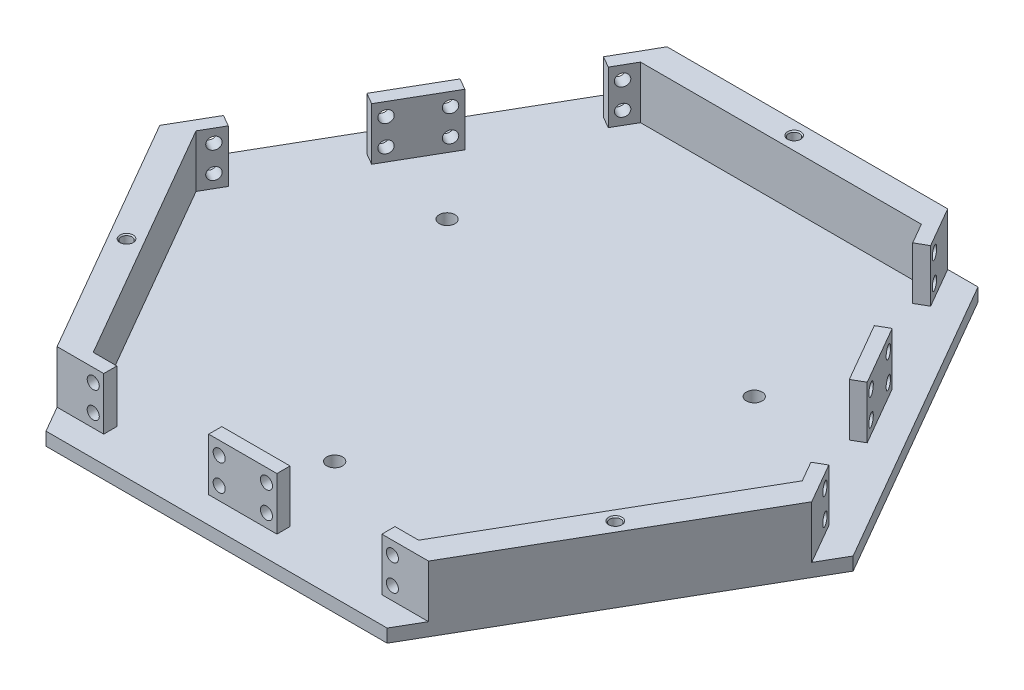
SolidWorks part; units mm, degrees
ref_plane "前视基准面" through (0, 0, 0) normal (0, 0, 1) x (1, 0, 0)
ref_plane "上视基准面" through (0, 0, 0) normal (0, 1, 0) x (1, 0, 0)
ref_plane "右视基准面" through (0, 0, 0) normal (1, 0, 0) x (0, 0, -1)
other "Configuration Table"
sketch "草图6" plane through (0, 0, 0) normal (0, 1, 0) x (1, 0, 0)
  line L1 (130, 0) -> (65, 112.5833)
  line L2 (65, 112.5833) -> (-65, 112.5833)
  line L3 (-65, 112.5833) -> (-130, 0)
  line L4 (-130, 0) -> (-65, -112.5833)
  line L5 (-65, -112.5833) -> (65, -112.5833)
  line L6 (65, -112.5833) -> (130, 0)
  circle A0 centre (0, 0) radius 112.5833 construction
  dimension "D1" = 130
extrude "凸台-拉伸5" add sketch "草图6" along normal blind 5
sketch "草图7" plane through (0, 5, 0) normal (0, 1, 0) x (1, 0, 0)
  line L0 (-53, -112.5833) -> (-13, -112.5833) construction
  line L1 (-53, -112.5833) -> (-53, -72.5833) construction
  line L2 (-13, -112.5833) -> (-13, -72.5833) construction
  line L3 (-53, -72.5833) -> (-13, -72.5833) construction
  line L4 (-65, -112.5833) -> (65, -112.5833) construction
  line L5 (13, -112.5833) -> (53, -112.5833) construction
  line L6 (13, -112.5833) -> (13, -72.5833) construction
  line L7 (53, -112.5833) -> (53, -72.5833) construction
  line L8 (13, -72.5833) -> (53, -72.5833) construction
  line L9 (-71, 102.191) -> (-91, 67.55) construction
  line L10 (-71, 102.191) -> (-36.359, 82.191) construction
  line L11 (-91, 67.55) -> (-56.359, 47.55) construction
  line L12 (-36.359, 82.191) -> (-56.359, 47.55) construction
  line L13 (-65, 112.5833) -> (-130, 0) construction
  line L14 (-104, 45.0333) -> (-124, 10.3923) construction
  line L15 (-104, 45.0333) -> (-69.359, 25.0333) construction
  line L16 (-124, 10.3923) -> (-89.359, -9.6077) construction
  line L17 (-69.359, 25.0333) -> (-89.359, -9.6077) construction
  line L18 (71, 102.191) -> (91, 67.55) construction
  line L19 (71, 102.191) -> (36.359, 82.191) construction
  line L20 (91, 67.55) -> (56.359, 47.55) construction
  line L21 (36.359, 82.191) -> (56.359, 47.55) construction
  line L22 (130, 0) -> (65, 112.5833) construction
  line L23 (104, 45.0333) -> (124, 10.3923) construction
  line L24 (104, 45.0333) -> (69.359, 25.0333) construction
  line L25 (124, 10.3923) -> (89.359, -9.6077) construction
  line L26 (69.359, 25.0333) -> (89.359, -9.6077) construction
  line L27 (-4, -97.5833) -> (4, -97.5833)
  line L28 (-53, -97.5833) -> (-53, -102.5833)
  line L29 (-53, -97.5833) -> (-62, -97.5833)
  line L30 (-53, -102.5833) -> (-62, -102.5833)
  line L31 (-62, -97.5833) -> (-62, -102.5833)
  line L32 (-13, -97.5833) -> (-4, -97.5833)
  line L33 (-13, -97.5833) -> (-13, -102.5833)
  line L34 (-4, -97.5833) -> (-4, -102.5833)
  line L35 (-13, -102.5833) -> (-4, -102.5833)
  line L36 (0, -112.5833) -> (0, 112.5833) construction
  line L37 (65, 112.5833) -> (-65, 112.5833) construction
  line L38 (-115.3397, 5.3923) -> (-111.0096, 2.8923)
  line L39 (-115.3397, 5.3923) -> (-119.8397, -2.4019)
  line L40 (-111.0096, 2.8923) -> (-115.5096, -4.9019)
  line L41 (-119.8397, -2.4019) -> (-115.5096, -4.9019)
  line L42 (-95.3397, 40.0333) -> (-91.0096, 37.5333)
  line L43 (-95.3397, 40.0333) -> (-90.3397, 48.6936)
  line L44 (-91.0096, 37.5333) -> (-86.0096, 46.1936)
  line L45 (-90.3397, 48.6936) -> (-86.0096, 46.1936)
  line L46 (-82.3397, 62.55) -> (-78.0096, 60.05)
  line L47 (-82.3397, 62.55) -> (-86.8397, 54.7558)
  line L48 (-78.0096, 60.05) -> (-82.5096, 52.2558)
  line L49 (-86.8397, 54.7558) -> (-82.5096, 52.2558)
  line L50 (-62.3397, 97.191) -> (-58.0096, 94.691)
  line L51 (-62.3397, 97.191) -> (-57.8397, 104.9852)
  line L52 (-58.0096, 94.691) -> (-53.5096, 102.4852)
  line L53 (-57.8397, 104.9852) -> (-53.5096, 102.4852)
  line L54 (58.0096, 94.691) -> (53.5096, 102.4852)
  line L55 (57.8397, 104.9852) -> (53.5096, 102.4852)
  line L56 (62.3397, 97.191) -> (57.8397, 104.9852)
  line L57 (62.3397, 97.191) -> (58.0096, 94.691)
  line L58 (78.0096, 60.05) -> (82.5096, 52.2558)
  line L59 (86.8397, 54.7558) -> (82.5096, 52.2558)
  line L60 (82.3397, 62.55) -> (86.8397, 54.7558)
  line L61 (82.3397, 62.55) -> (78.0096, 60.05)
  line L62 (91.0096, 37.5333) -> (86.0096, 46.1936)
  line L63 (90.3397, 48.6936) -> (86.0096, 46.1936)
  line L64 (95.3397, 40.0333) -> (90.3397, 48.6936)
  line L65 (95.3397, 40.0333) -> (91.0096, 37.5333)
  line L66 (111.0096, 2.8923) -> (115.5096, -4.9019)
  line L67 (119.8397, -2.4019) -> (115.5096, -4.9019)
  line L68 (115.3397, 5.3923) -> (119.8397, -2.4019)
  line L69 (115.3397, 5.3923) -> (111.0096, 2.8923)
  line L70 (53, -102.5833) -> (62, -102.5833)
  line L71 (62, -97.5833) -> (62, -102.5833)
  line L72 (53, -97.5833) -> (62, -97.5833)
  line L73 (53, -97.5833) -> (53, -102.5833)
  line L74 (4, -97.5833) -> (4, -102.5833)
  line L75 (13, -102.5833) -> (4, -102.5833)
  line L76 (13, -97.5833) -> (13, -102.5833)
  line L77 (13, -97.5833) -> (4, -97.5833)
  line L78 (-4, -97.5833) -> (-4, -102.5833)
  line L79 (4, -97.5833) -> (4, -102.5833)
  line L80 (-4, -102.5833) -> (4, -102.5833)
  line L81 (86.8397, 54.7558) -> (90.3397, 48.6936)
  line L82 (86.8397, 54.7558) -> (82.5096, 52.2558)
  line L83 (90.3397, 48.6936) -> (86.0096, 46.1936)
  line L84 (82.5096, 52.2558) -> (86.0096, 46.1936)
  line L85 (-82.5096, 52.2558) -> (-86.0096, 46.1936)
  line L86 (-82.5096, 52.2558) -> (-86.8397, 54.7558)
  line L87 (-86.0096, 46.1936) -> (-90.3397, 48.6936)
  line L88 (-86.8397, 54.7558) -> (-90.3397, 48.6936)
  dimension "D1" = 40
  dimension "D2" = 40
  dimension "D3" = 40
  dimension "D4" = 40
  dimension "D5" = 40
  dimension "D6" = 40
  dimension "D7" = 40
  dimension "D8" = 40
  dimension "D9" = 40
  dimension "D10" = 40
  dimension "D11" = 40
  dimension "D12" = 40
  dimension "D13" = 12
  dimension "D14" = 12
  dimension "D15" = 12
  dimension "D16" = 12
  dimension "D17" = 12
  dimension "D18" = 12
  dimension "D19" = 9
  dimension "D20" = 5
  dimension "D21" = 10
  dimension "D22" = 10
  dimension "D23" = 9
  dimension "D24" = 9
  dimension "D25" = 5
  dimension "D26" = 10
  dimension "D27" = 10
  dimension "D28" = 5
  dimension "D29" = 10
  dimension "D30" = 9
  dimension "D31" = 10
  dimension "D32" = 5
  dimension "D33" = 10
  dimension "D34" = 5
  dimension "D35" = 9
extrude "凸台-拉伸6" add sketch "草图7" along normal blind 20 contours L72 L73 L70 L71 | L76 L77 L74 L75 | L34 L80 L74 L27 | L33 L35 L34 L32 | L29 L31 L30 L28 | L68 L69 L66 L67 | L65 L64 L63 L62 | L59 L84 L63 L81 | L60 L61 L58 L59 | L57 L56 L55 L54 | L53 L51 L50 L52 | L47 L49 L48 L46 | L49 L88 L45 L85 | L45 L43 L42 L44 | L39 L41 L40 L38
sketch "草图9" plane through (0, 0, 102.5833) normal (0, 0, 1) x (1, 0, 0)
  line L0 (-57, 25) -> (-57, 5) construction
  line L1 (-53, 25) -> (-62, 25) construction
  line L2 (-53, 5) -> (-62, 5) construction
  line L3 (-9, 25) -> (-9, 5) construction
  line L4 (13, 25) -> (-13, 25) construction
  line L5 (13, 5) -> (-13, 5) construction
  line L6 (9, 25) -> (9, 5) construction
  line L7 (-65, 5) -> (65, 5) construction
  line L8 (57, 25) -> (57, 5) construction
  line L9 (53, 25) -> (62, 25) construction
  line L10 (-53, 25) -> (-53, 5) construction
  line L11 (-13, 25) -> (-13, 5) construction
  line L12 (13, 25) -> (13, 5) construction
  line L13 (0, 25) -> (0, 5) construction
  line L14 (53, 25) -> (53, 5) construction
  circle A0 centre (-57, 20) radius 2.3
  circle A1 centre (-57, 10) radius 2.3
  circle A2 centre (-9, 20) radius 2.3
  circle A3 centre (-9, 10) radius 2.3
  circle A4 centre (9, 20) radius 2.3
  circle A5 centre (9, 10) radius 2.3
  circle A6 centre (57, 20) radius 2.3
  circle A7 centre (57, 10) radius 2.3
  dimension "D5" = 5
  dimension "D1" = 4
  dimension "D2" = 4
  dimension "D3" = 4
  dimension "D4" = 4
  dimension "D6" = 10
  dimension "D7" = 5
  dimension "D8" = 10
  dimension "D9" = 10
  dimension "D10" = 5
  dimension "D11" = 5
  dimension "D12" = 10
sketch "草图10" plane through (0, 5, 0) normal (0, 1, 0) x (1, 0, 0)
  line L0 (-115.5096, -4.9019) -> (-62, -97.5833)
  line L3 (-115.5096, -4.9019) -> (-119.8397, -2.4019)
  line L5 (62, -97.5833) -> (115.5096, -4.9019)
  line L6 (115.5096, -4.9019) -> (119.8397, -2.4019)
  line L8 (57.8397, 104.9852) -> (53.5096, 102.4852)
  line L9 (57.8397, 104.9852) -> (53.5096, 102.4852) construction
  line L10 (53.5096, 102.4852) -> (-53.5096, 102.4852)
  line L11 (-58.0096, 94.691) -> (-53.5096, 102.4852) construction
  line L23 (-62, -102.5833) -> (-70.7735, -102.5833)
  line L24 (-130, 0) -> (-65, -112.5833) construction
  line L25 (-119.8397, -2.4019) -> (-124.2265, -10)
  line L27 (62, -102.5833) -> (70.7735, -102.5833)
  line L28 (65, -112.5833) -> (130, 0) construction
  line L29 (70.7735, -102.5833) -> (124.2265, -10)
  line L36 (124.2265, -10) -> (119.8397, -2.4019)
  line L37 (-70.7735, -102.5833) -> (-124.2265, -10)
  line L38 (65, 112.5833) -> (-65, 112.5833) construction
  line L39 (57.8397, 104.9852) -> (53.453, 112.5833)
  line L40 (53.453, 112.5833) -> (-53.5096, 112.5833)
  line L42 (62, -97.5833) -> (62, -102.5833)
  line L43 (-62, -97.5833) -> (-62, -102.5833)
  line L44 (-53.5096, 112.5833) -> (-57.8397, 104.9852)
  line L45 (-57.8397, 104.9852) -> (-53.5096, 102.4852)
extrude "凸台-拉伸7" add sketch "草图10" along normal blind 20
sketch "草图11" plane through (88.8397, 0, -51.2917) normal (0.866, 0, -0.5) x (-0.5, 0, -0.866)
  line L0 (-57, 25) -> (-57, 5) construction
  line L1 (-53, 25) -> (-70.7735, 25) construction
  line L2 (-53, 5) -> (-70.7735, 5) construction
  line L3 (-9, 25) -> (-9, 5) construction
  line L4 (-13, 25) -> (13, 25) construction
  line L5 (-65, 5) -> (65, 5) construction
  line L6 (57, 25) -> (57, 5) construction
  line L7 (-53, 25) -> (-70.7735, 25) construction
  line L8 (9, 25) -> (9, 5) construction
  line L10 (0, 25) -> (0, 5) construction
  circle A0 centre (-57, 20) radius 2.3
  circle A1 centre (-57, 9.8476) radius 2.3
  circle A2 centre (-9, 20) radius 2.3
  circle A3 centre (-9, 9.8476) radius 2.3
  circle A4 centre (9, 9.8476) radius 2.3
  circle A5 centre (9, 20) radius 2.3
  circle A6 centre (57, 9.8476) radius 2.3
  circle A7 centre (57, 20) radius 2.3
  dimension "D1" = 4
  dimension "D2" = 4
  dimension "D3" = 5
  dimension "D4" = 5
sketch "草图13" plane through (-88.8397, 0, -51.2917) normal (-0.866, 0, -0.5) x (-0.5, 0, 0.866)
  line L0 (-57, 25) -> (-57, 5) construction
  line L1 (-53, 25) -> (-62, 25) construction
  line L2 (-65, 5) -> (65, 5) construction
  line L3 (0, 25) -> (0, 5) construction
  line L4 (-13, 25) -> (13, 25) construction
  line L5 (-9, 25) -> (-9, 5) construction
  line L6 (-13, 5) -> (13, 5) construction
  circle A0 centre (-57, 20) radius 2.3
  circle A1 centre (-57, 10) radius 2.3
  circle A2 centre (-9, 20) radius 2.3
  circle A3 centre (-9, 10) radius 2.3
  circle A4 centre (9, 10) radius 2.3
  circle A5 centre (9, 20) radius 2.3
  circle A6 centre (57, 10) radius 2.3
  circle A7 centre (57, 20) radius 2.3
  dimension "D3" = 5
  dimension "D5" = 10
  dimension "D1" = 4
  dimension "D2" = 4
  dimension "D4" = 10
  dimension "D6" = 5
extrude "切除-拉伸2" cut sketch "草图13" against normal blind 20
extrude "切除-拉伸3" cut sketch "草图9" against normal blind 20
extrude "切除-拉伸4" cut sketch "草图11" against normal blind 20
sketch "草图16" plane through (0, 5, 0) normal (0, 1, 0) x (1, 0, 0)
  line L0 (0, 112.5833) -> (0, -112.5833) construction
  line L2 (-65, -112.5833) -> (65, -112.5833) construction
  line L3 (-97.5, -56.2917) -> (97.5, 56.2917) construction
  line L6 (-124.2265, -10) -> (-70.7735, -102.5833) construction
  line L9 (130, 0) -> (65, 112.5833) construction
  line L10 (97.5, -56.2917) -> (-97.5, 56.2917) construction
  line L11 (70.7735, -102.5833) -> (124.2265, -10) construction
  line L12 (-65, 112.5833) -> (-130, 0) construction
  circle A3 centre (0, -67.5833) radius 3
  circle A4 centre (58.5289, 33.7917) radius 3
  circle A5 centre (-58.5289, 33.7917) radius 3
  dimension "D1" = 45
  dimension "D2" = 45
  dimension "D3" = 45
extrude "切除-拉伸5" cut sketch "草图16" against normal blind 5
sketch "草图18" plane through (0, 25, 0) normal (0, 1, 0) x (1, 0, 0)
  line L0 (-97.5, -56.2917) -> (-88.7548, -51.2426) construction
  line L1 (-124.2265, -10) -> (-70.7735, -102.5833) construction
  line L2 (-62, -97.5833) -> (-115.5096, -4.9019) construction
  line L3 (97.5, -56.2917) -> (88.7548, -51.2426) construction
  line L4 (70.7735, -102.5833) -> (124.2265, -10) construction
  line L5 (115.5096, -4.9019) -> (62, -97.5833) construction
  line L6 (-0.0283, 112.5833) -> (0, 102.4852) construction
  line L7 (53.453, 112.5833) -> (-53.5096, 112.5833) construction
  line L8 (-53.5096, 102.4852) -> (53.5096, 102.4852) construction
  circle A0 centre (-93.1274, -53.7671) radius 2.5
  circle A1 centre (93.1274, -53.7671) radius 2.5
  circle A2 centre (-0.0142, 107.5343) radius 2.5
  point P18 (-93.1274, -53.7671)
  point P20 (93.1274, -53.7671)
  point P22 (-0.0142, 107.5343)
  point P34 (-93.1274, -53.7671)
  point P36 (93.1274, -53.7671)
  point P39 (-93.1274, -53.7671)
  point P42 (-93.1274, -53.7671)
  point P44 (93.1274, -53.7671)
  point P46 (-0.0142, 107.5343)
  point P48 (93.1274, -53.7671)
  point P50 (93.1274, -53.7671)
  dimension "D1" = 5.049
  dimension "D2" = 186.2548
hole_wizard "M5 螺纹孔1" positions "草图18" profile "草图30" tap size "M5" standard "GB" end condition through all
sketch "草图30" plane through (93.1274, 25, 53.7671) normal (1, 0, 0) x (0, 0, 1)
  line L0 (0, 0) -> (0, 25)
  line L1 (0, 25) -> (2.1, 25)
  line L2 (2.1, 25) -> (2.1, 0.425)
  line L3 (2.1, 0.425) -> (2.525, 0)
  line L5 (2.525, 0) -> (0, 0)
  line L6 (-2.1, 0.425) -> (-2.525, 0) construction
  line L11 (0, -6.35) -> (0, 107.95) construction
  dimension "通孔螺纹孔钻头直径" = 4.2
  dimension "通孔螺纹孔钻头深度" = 25
  dimension "近端锥形沉头孔直径" = 5.05
  dimension "近端锥形沉头孔角度" = 90
cosmetic thread "孔螺蚊线15" parameters "D2"=5
cosmetic thread "孔螺蚊线17" parameters "D2"=5
cosmetic thread "孔螺蚊线18" parameters "D2"=5
